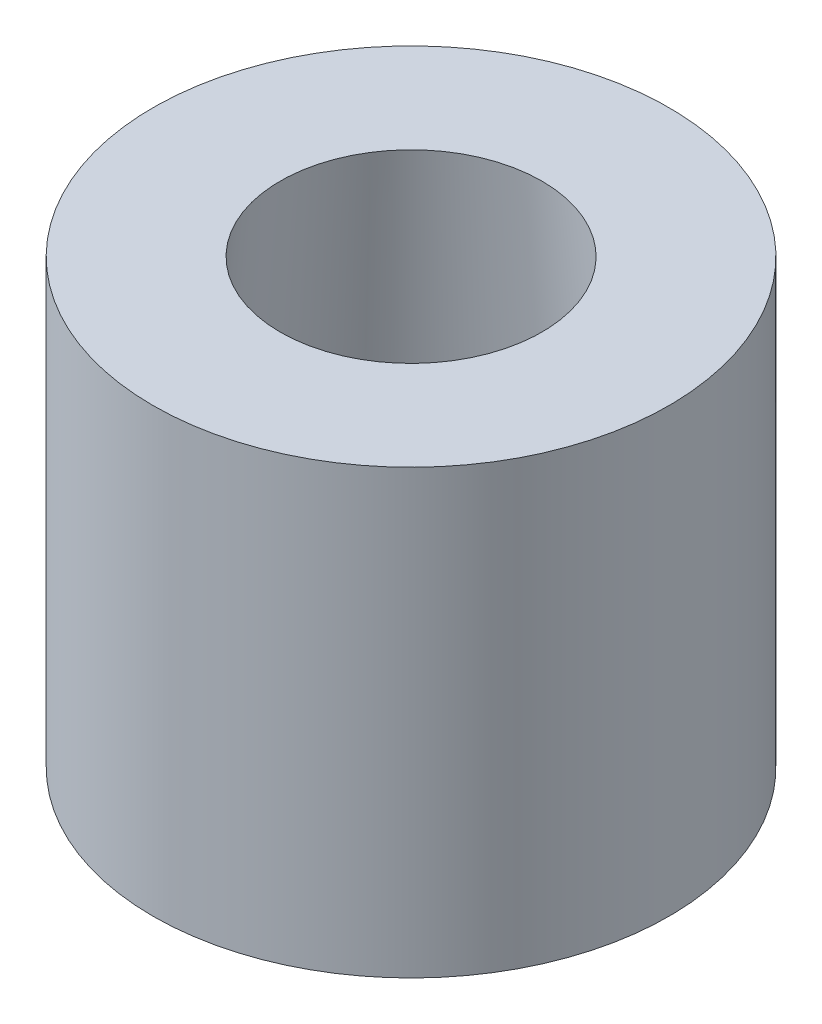
SolidWorks part; units mm, degrees
ref_plane "Front Plane" through (0, 0, 0) normal (0, 0, 1) x (1, 0, 0)
ref_plane "Top Plane" through (0, 0, 0) normal (0, 1, 0) x (1, 0, 0)
ref_plane "Right Plane" through (0, 0, 0) normal (1, 0, 0) x (0, 0, -1)
sketch "Sketch2" plane through (0, 0, 0) normal (0, 1, 0) x (1, 0, 0)
  circle A0 centre (0, 0) radius 17.5
extrude "Boss-Extrude2" add sketch "Sketch2" along normal blind 30
sketch "Sketch3" plane through (0, 0, 0) normal (0, -1, 0) x (1, 0, 0)
  circle A0 centre (0, 0) radius 11.5
extrude "Cut-Extrude1" cut sketch "Sketch3" against normal blind 30 draft 5
sketch "Sketch4" plane through (0, 0, 0) normal (0, -1, 0) x (1, 0, 0)
  circle A0 centre (0, 0.4395) radius 12.5
  circle A1 centre (0, 0.4395) radius 15
extrude "Cut-Extrude2" cut sketch "Sketch4" against normal blind 5
